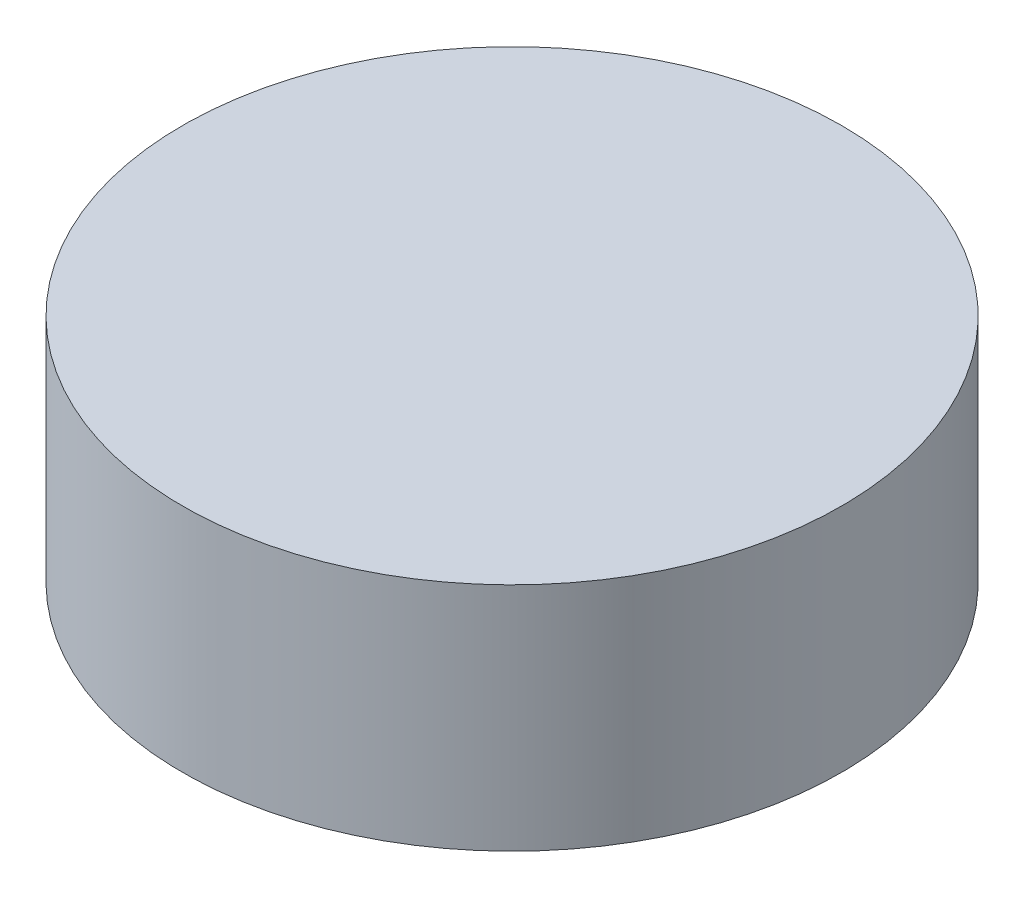
SolidWorks part; units mm, degrees
ref_plane "Alzado" through (0, 0, 0) normal (0, 0, 1) x (1, 0, 0)
ref_plane "Planta" through (0, 0, 0) normal (0, 1, 0) x (1, 0, 0)
ref_plane "Vista lateral" through (0, 0, 0) normal (1, 0, 0) x (0, 0, -1)
ref_plane "Plano_TacoPVC2" through (0, 18, 0) normal (0, 1, 0) x (1, 0, 0)
sketch "SkTacoPVC2" plane through (0, 18, 0) normal (0, 1, 0) x (1, 0, 0)
  circle A0 centre (-75, 129.9038) radius 20
extrude "TacoPVC2" add sketch "SkTacoPVC2" along normal blind 14 separate body
